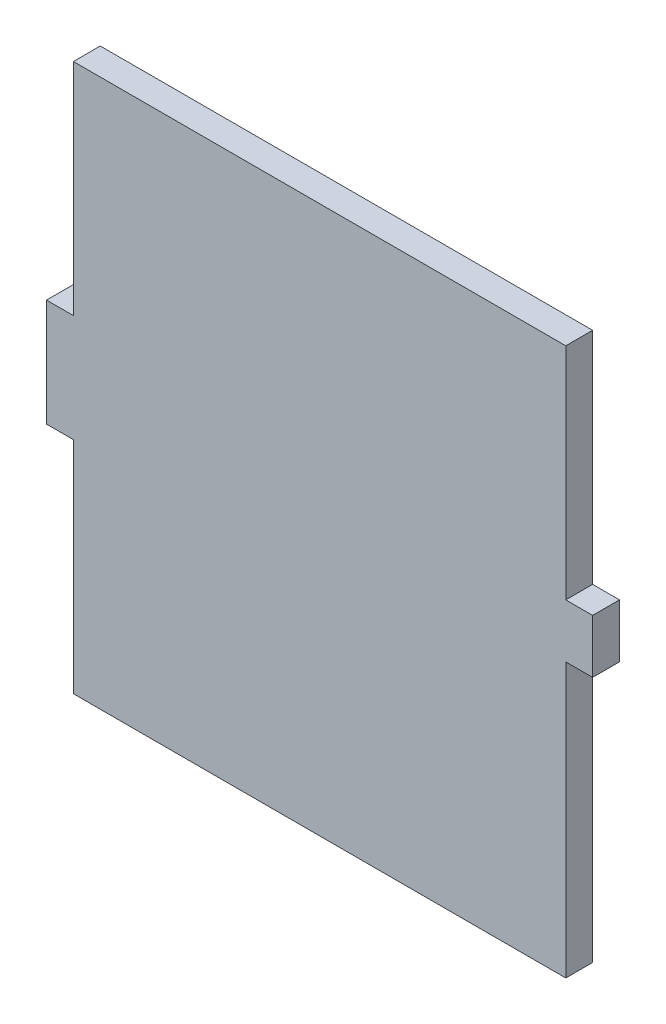
SolidWorks part; units mm, degrees
ref_plane "Přední rovina" through (0, 0, 0) normal (0, 0, 1) x (1, 0, 0)
ref_plane "Horní rovina" through (0, 0, 0) normal (0, 1, 0) x (1, 0, 0)
ref_plane "Pravá rovina" through (0, 0, 0) normal (1, 0, 0) x (0, 0, -1)
sketch "Skica1" plane through (0, 0, 0) normal (0, 0, 1) x (1, 0, 0)
  line L0 (55, -30.58) -> (55, -61.16)
  line L1 (0, 0) -> (55, 0)
  line L2 (0, 0) -> (0, -24.58)
  line L3 (0, -61.16) -> (55, -61.16)
  line L4 (55, 0) -> (55, -24.58)
  line L5 (0, -24.58) -> (-3, -24.58)
  line L6 (0, -36.58) -> (-3, -36.58)
  line L7 (-3, -24.58) -> (-3, -36.58)
  line L8 (55, -24.58) -> (58, -24.58)
  line L9 (55, -30.58) -> (58, -30.58)
  line L10 (58, -24.58) -> (58, -30.58)
  line L11 (0, -36.58) -> (0, -61.16)
  dimension "D1" = 55
  dimension "D2" = 61.16
  dimension "D3" = 24.58
  dimension "D4" = 0
  dimension "D5" = 6
  dimension "D6" = 12
  dimension "D7" = 3
  dimension "D8" = 3
  dimension "D9" = 24.58
extrude "Přidat vysunutím1" add sketch "Skica1" along normal blind 3
